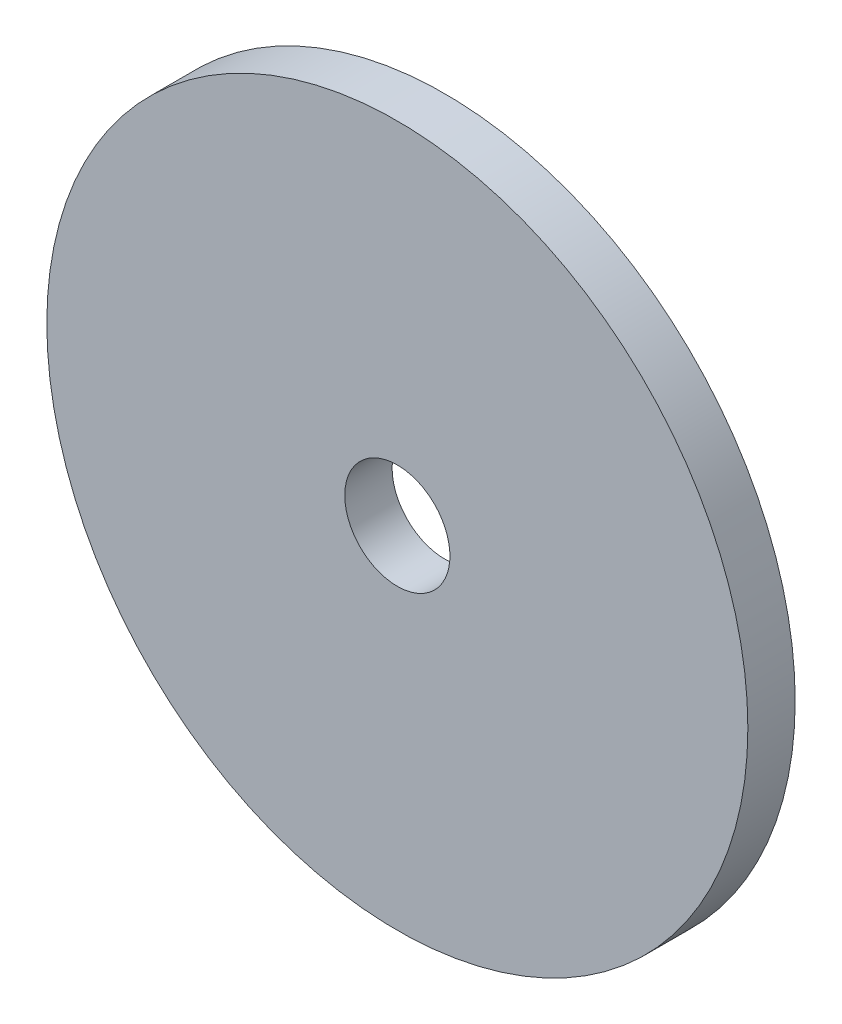
SolidWorks part; units mm, degrees
ref_plane "Front Plane" through (0, 0, 0) normal (0, 0, 1) x (1, 0, 0)
ref_plane "Top Plane" through (0, 0, 0) normal (0, 1, 0) x (1, 0, 0)
ref_plane "Right Plane" through (0, 0, 0) normal (1, 0, 0) x (0, 0, -1)
sketch "Sketch1" plane through (0, 0, 0) normal (0, 0, 1) x (1, 0, 0)
  circle A0 centre (-26.0075, -4.9686) radius 3
  circle A1 centre (-26.0075, -4.9686) radius 20
  dimension "D1" = 6
  dimension "D2" = 40
extrude "Boss-Extrude1" add sketch "Sketch1" along normal blind 2.7
